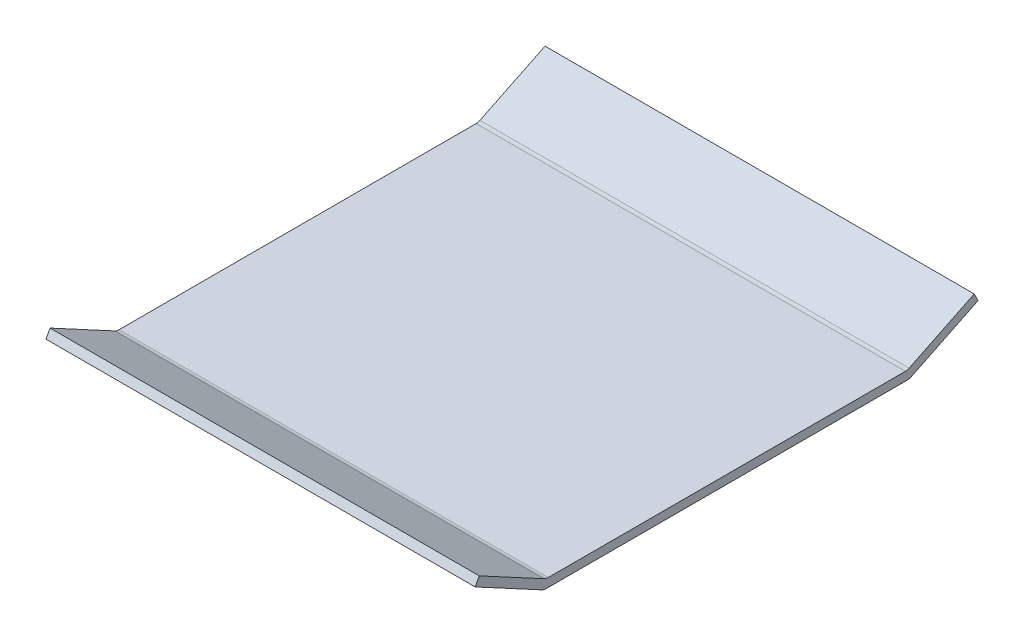
SolidWorks part; units mm, degrees
ref_plane "Front Plane" through (0, 0, 0) normal (0, 0, 1) x (1, 0, 0)
ref_plane "Top Plane" through (0, 0, 0) normal (0, 1, 0) x (1, 0, 0)
ref_plane "Right Plane" through (0, 0, 0) normal (1, 0, 0) x (0, 0, -1)
sketch "Sketch2" plane through (0, 0, 0) normal (1, 0, 0) x (0, 0, -1)
  line L0 (223.2867, 31.5031) -> (247.2781, 18.5982) construction
  line L1 (248.7822, 18.2193) -> (380.8921, 18.2193) construction
  line L2 (382.2834, 18.5404) -> (406.3662, 30.2805) construction
  line L3 (406.3662, 30.2805) -> (407.7575, 27.4266) construction
  line L4 (383.016, 15.3654) -> (407.7575, 27.4266) construction
  line L5 (247.9824, 15.0443) -> (381.6248, 15.0443) construction
  line L6 (221.7827, 28.707) -> (246.4784, 15.4232) construction
  line L7 (221.7827, 28.707) -> (223.2867, 31.5031) construction
  line L8 (223.2867, 31.5031) -> (247.2781, 18.5982)
  line L9 (248.7822, 18.2193) -> (380.8921, 18.2193)
  line L10 (382.2834, 18.5404) -> (406.3662, 30.2805)
  line L11 (406.3662, 30.2805) -> (407.7575, 27.4266)
  line L12 (383.016, 15.3654) -> (407.7575, 27.4266)
  line L13 (247.9824, 15.0443) -> (381.6248, 15.0443)
  line L14 (221.7827, 28.707) -> (246.4784, 15.4232)
  line L15 (221.7827, 28.707) -> (223.2867, 31.5031)
  arc A0 (247.2781, 18.5982) -> (248.7822, 18.2193) centre (248.7822, 21.3943) ccw construction
  arc A1 (380.8921, 18.2193) -> (382.2834, 18.5404) centre (380.8921, 21.3943) ccw construction
  arc A2 (381.6248, 15.0443) -> (383.016, 15.3654) centre (381.6248, 18.2193) ccw construction
  arc A3 (246.4784, 15.4232) -> (247.9824, 15.0443) centre (247.9824, 18.2193) ccw construction
  arc A4 (247.2781, 18.5982) -> (248.7822, 18.2193) centre (248.7822, 21.3943) ccw
  arc A5 (380.8921, 18.2193) -> (382.2834, 18.5404) centre (380.8921, 21.3943) ccw
  arc A6 (381.6248, 15.0443) -> (383.016, 15.3654) centre (381.6248, 18.2193) ccw
  arc A7 (246.4784, 15.4232) -> (247.9824, 15.0443) centre (247.9824, 18.2193) ccw
extrude "Boss-Extrude1" add sketch "Sketch2" against normal blind 158.75 from offset 50.8
